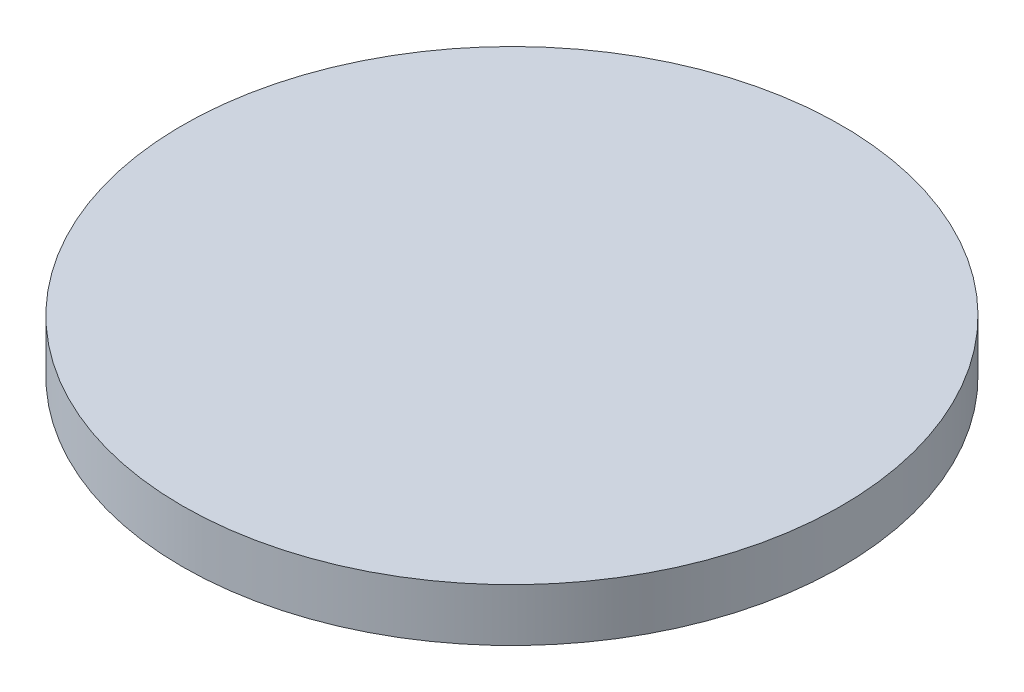
SolidWorks part; units mm, degrees
ref_plane "Front Plane" through (0, 0, 0) normal (0, 0, 1) x (1, 0, 0)
ref_plane "Top Plane" through (0, 0, 0) normal (0, 1, 0) x (1, 0, 0)
ref_plane "Right Plane" through (0, 0, 0) normal (1, 0, 0) x (0, 0, -1)
sketch "Sketch1" plane through (0, 0, 0) normal (0, 1, 0) x (1, 0, 0)
  circle A0 centre (0, 0) radius 25
  dimension "D1" = 50
extrude "Boss-Extrude1" add sketch "Sketch1" along normal blind 4
sketch "Sketch2" plane through (0, 0, 0) normal (0, -1, 0) x (1, 0, 0)
  line L7 (-2.2583, 0.95) -> (-0.95, 0.95)
  line L8 (-0.95, 2.2583) -> (-0.95, 0.95)
  line L11 (2.2583, 0.95) -> (0.95, 0.95)
  line L12 (0.95, 2.2583) -> (0.95, 0.95)
  line L15 (2.2583, -0.95) -> (0.95, -0.95)
  line L16 (0.95, -2.2583) -> (0.95, -0.95)
  line L19 (-2.2583, -0.95) -> (-0.95, -0.95)
  line L20 (-0.95, -2.2583) -> (-0.95, -0.95)
  circle A0 centre (0, 0) radius 4
  arc A1 (-0.95, -2.2583) -> (0.95, -2.2583) centre (0, 0) ccw
  arc A2 (-2.2583, 0.95) -> (-2.2583, -0.95) centre (0, 0) ccw
  arc A3 (0.95, 2.2583) -> (-0.95, 2.2583) centre (0, 0) ccw
  arc A4 (2.2583, -0.95) -> (2.2583, 0.95) centre (0, 0) ccw
  dimension "D1" = 8
  dimension "D2" = 4.9
  dimension "D7" = 0.95
  dimension "D8" = 0.95
  dimension "D9" = 0.95
  dimension "D10" = 0.95
  dimension "D11" = 0.95
  dimension "D12" = 0.95
  dimension "D13" = 0.95
  dimension "D14" = 0.95
extrude "Boss-Extrude2" add sketch "Sketch2" along normal blind 8
